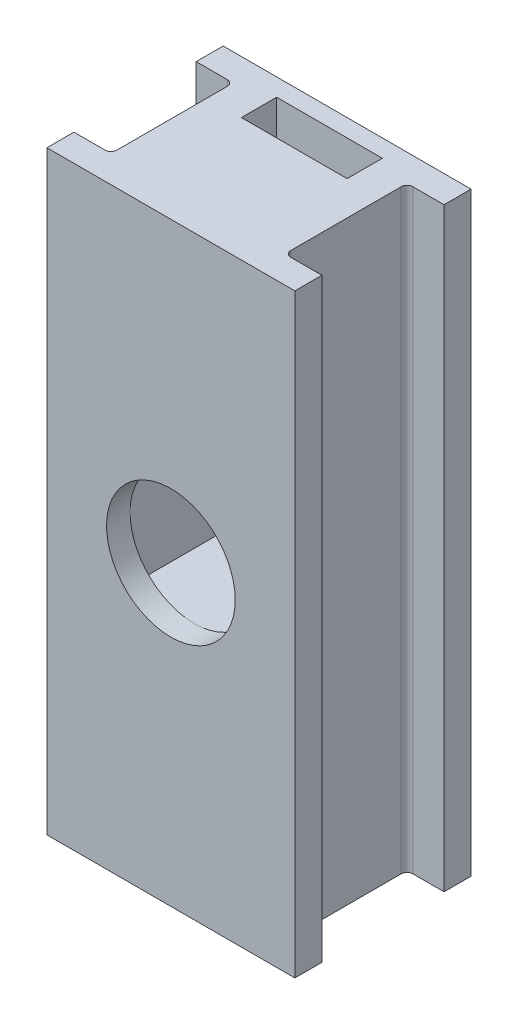
SolidWorks part; units mm, degrees
ref_plane "Front Plane" through (0, 0, 0) normal (0, 0, 1) x (1, 0, 0)
ref_plane "Top Plane" through (0, 0, 0) normal (0, 1, 0) x (1, 0, 0)
ref_plane "Right Plane" through (0, 0, 0) normal (1, 0, 0) x (0, 0, -1)
sketch "Sketch1" plane through (0, 0, 0) normal (0, 0, 1) x (1, 0, 0)
  line L0 (5.55, 29.125) -> (-5.55, 29.125)
  line L1 (5.55, 8.125) -> (5.55, 29.125)
  line L2 (-5.55, 8.125) -> (5.55, 8.125)
  line L3 (-5.55, 29.125) -> (-5.55, 8.125)
  line L4 (10.55, -18.525) -> (-10.55, -18.525)
  line L5 (10.55, -18.525) -> (10.55, 32.125)
  line L6 (10.55, 32.125) -> (-10.55, 32.125)
  line L7 (5.55, 5.475) -> (-5.55, 5.475)
  line L8 (5.55, -15.525) -> (5.55, 5.475)
  line L9 (-5.55, -15.525) -> (5.55, -15.525)
  line L10 (-5.55, 5.475) -> (-5.55, -15.525)
  line L11 (-10.55, -18.525) -> (-10.55, 32.125)
  line L12 (-7.55, 15.35) -> (-7.55, -36.6)
  line L13 (7.55, 15.35) -> (7.55, -36.6)
  line L14 (-7.4, 15.35) -> (-7.4, -36.6)
  line L15 (7.4, 15.35) -> (7.4, -36.6)
  circle A0 centre (0, 0) radius 5.475
  circle A1 centre (0, 13.6) radius 5.475
  point P24 (0, 0)
sketch "Sketch2" plane through (0, 0, 0) normal (0, 0, 1) x (1, 0, 0)
  line L0 (-10.55, -18.525) -> (-10.55, 32.125) construction
  line L1 (10.55, 32.125) -> (-10.55, 32.125) construction
  line L2 (10.55, -18.525) -> (10.55, 32.125) construction
  line L3 (10.55, -18.525) -> (-10.55, -18.525) construction
  line L4 (-10.55, -18.525) -> (-10.55, 32.125)
  line L5 (10.55, 32.125) -> (-10.55, 32.125)
  line L6 (10.55, -18.525) -> (10.55, 32.125)
  line L7 (10.55, -18.525) -> (-10.55, -18.525)
  line L8 (0, 13.6) -> (0, 0) construction
  circle A0 centre (0, 0) radius 5.475 construction
  circle A1 centre (0, 13.6) radius 5.475 construction
  circle A2 centre (0, 0) radius 5.475 construction
  circle A3 centre (0, 13.6) radius 5.475 construction
  circle A4 centre (0, 6.8) radius 5.475
  point P10 (-7.4, 15.35)
  point P11 (7.4, 15.35)
  point P16 (0, 6.8)
extrude "Boss-Extrude1" add sketch "Sketch2" along normal mid plane 15
sketch "Sketch3" plane through (0, 32.125, 0) normal (0, 1, 0) x (1, 0, 0)
  line L0 (-10.55, -7.5) -> (-10.55, 7.5) construction
  line L1 (-10.55, 5.2) -> (-7.4, 5.2)
  line L2 (-10.55, 5.2) -> (-10.55, -5.2)
  line L3 (-10.55, -5.2) -> (-7.4, -5.2)
  line L4 (-7.4, 5.2) -> (-7.4, -5.2)
  point P6 (-10.55, 0)
  dimension "D1" = 10.4
extrude "Cut-Extrude1" cut sketch "Sketch3" against normal through all both and the other way through all
mirror "Mirror1" about plane through (0, 0, 0) normal (1, 0, 0) of "Cut-Extrude1"
sketch "Sketch4" plane through (0, 0, -7.5) normal (0, 0, -1) x (-1, 0, 0)
  line L0 (-5.55, -15.525) -> (-5.55, 5.475) construction
  line L1 (-5.55, 5.475) -> (5.55, 5.475) construction
  line L2 (5.55, 5.475) -> (5.55, -15.525) construction
  line L3 (5.55, -15.525) -> (-5.55, -15.525) construction
  line L4 (-5.55, 8.125) -> (-5.55, 29.125) construction
  line L5 (-5.55, 29.125) -> (5.55, 29.125) construction
  line L6 (5.55, 29.125) -> (5.55, 8.125) construction
  line L7 (5.55, 8.125) -> (-5.55, 8.125) construction
  line L8 (-5.55, -15.525) -> (-5.55, 5.475) construction
  line L9 (-5.55, 5.475) -> (5.55, 5.475) construction
  line L10 (5.55, 5.475) -> (5.55, -15.525) construction
  line L11 (5.55, -15.525) -> (-5.55, -15.525) construction
  line L12 (-5.55, 8.125) -> (-5.55, 29.125) construction
  line L13 (-5.55, 29.125) -> (5.55, 29.125) construction
  line L14 (5.55, 29.125) -> (5.55, 8.125) construction
  line L15 (5.55, 8.125) -> (-5.55, 8.125) construction
  line L16 (-5.55, 1.325) -> (-5.55, 22.325)
  line L17 (-5.55, 22.325) -> (5.55, 22.325)
  line L18 (5.55, 22.325) -> (5.55, 1.325)
  line L19 (5.55, 1.325) -> (-5.55, 1.325)
  circle A0 centre (0, 6.8) radius 5.475 construction
  circle A1 centre (0, 6.8) radius 5.475 construction
  point P15 (0, 0)
  point P16 (0, 22.325)
  dimension "D1" = 11.1
  dimension "D2" = 21
fillet "Fillet1" radius 0.5 4 edges at (-7.4, 6.8, -5.2) (-7.4, 6.8, 5.2) (7.4, 6.8, -5.2) (7.4, 6.8, 5.2)
extrude "Cut-Extrude3" cut sketch "Sketch4" against normal blind 13
sketch "Sketch6" plane through (0, 0, -7.5) normal (0, 0, -1) x (-1, 0, 0)
  line L0 (5.55, 1.325) -> (5.55, 22.325) construction
  line L1 (-5.55, -1.175) -> (5.55, -1.175)
  line L2 (-5.55, -1.175) -> (-5.55, -20.1157)
  line L3 (-5.55, -20.1157) -> (5.55, -20.1157)
  line L4 (5.55, -1.175) -> (5.55, -20.1157)
  line L5 (-5.55, 22.325) -> (-5.55, 1.325) construction
  line L6 (-5.55, 1.325) -> (5.55, 1.325) construction
  dimension "D1" = 2.5
extrude "Cut-Extrude4" cut sketch "Sketch6" against normal up to surface (13 mm away) up to face at (0.9125, 9.2375, 5.5)
sketch "Sketch7" plane through (0, 0, 5.5) normal (0, 0, -1) x (-1, 0, 0)
  line L0 (5.55, 1.325) -> (5.55, 22.325) construction
  line L1 (-5.55, 22.325) -> (5.55, 22.325)
  line L2 (-5.55, 22.325) -> (-5.55, 17.325)
  line L3 (-5.55, 17.325) -> (5.55, 17.325)
  line L4 (5.55, 22.325) -> (5.55, 17.325)
  dimension "D1" = 5
extrude "Cut-Extrude5" cut sketch "Sketch7" against normal blind 1
sketch "Sketch8" plane through (0, 32.125, 0) normal (0, 1, 0) x (1, 0, 0)
  line L1 (-4.5, 6) -> (4.5, 6)
  line L2 (-4.5, 6) -> (-4.5, 3)
  line L3 (-4.5, 3) -> (4.5, 3)
  line L4 (4.5, 6) -> (4.5, 3)
  point P4 (0, 3)
  dimension "D1" = 3
  dimension "D2" = 3
  dimension "D3" = 9
extrude "Cut-Extrude6" cut sketch "Sketch8" against normal up to surface (9.8 mm away) up to face at (0, 22.325, -0.5)
